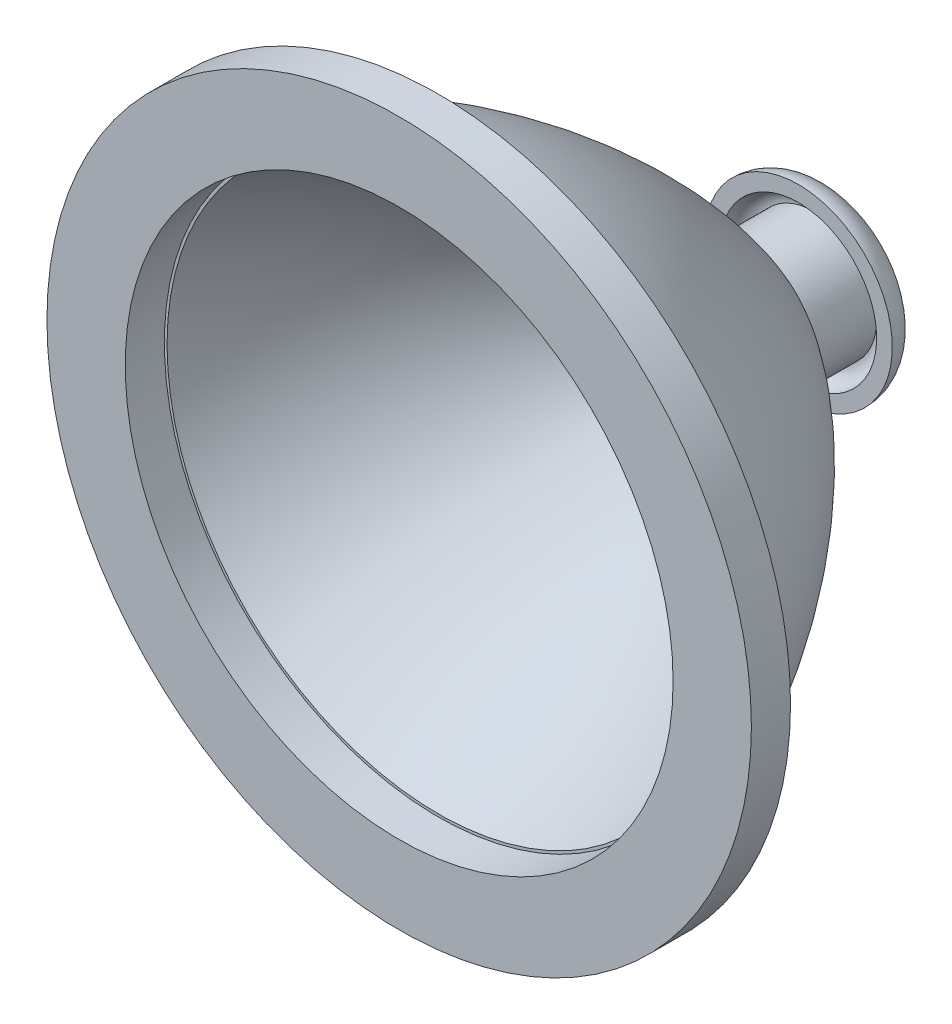
SolidWorks part; units mm, degrees
ref_plane "Front Plane" through (0, 0, 0) normal (0, 0, 1) x (1, 0, 0)
ref_plane "Top Plane" through (0, 0, 0) normal (0, 1, 0) x (1, 0, 0)
ref_plane "Right Plane" through (0, 0, 0) normal (1, 0, 0) x (0, 0, -1)
sketch "Sketch1" plane through (0, 0, 0) normal (1, 0, 0) x (0, 0, -1)
  line L0 (-22.4288, 0) -> (28.5775, 0) construction
  line L1 (0, 0) -> (0, 50.8)
  line L2 (0, 0) -> (50.8, 0)
  line L3 (50.8, 0) -> (50.8, 10.16)
  line L5 (0, 88.99) -> (0, -88.99) construction
  arc A0 (50.8, 10.16) -> (0, 50.8) centre (-34.7283, -44.6804) ccw
  dimension "D3" = 101.6
  dimension "D1" = 50.8
  dimension "D2" = 10.16
revolve "Base Revolve" add sketch "Sketch1" angle 360 about L0
shell "Lens Shell" thickness 6.35
sketch "Sketch2" plane through (0, 0, -50.8) normal (0, 0, -1) x (-1, 0, 0)
  circle A1 centre (0, 0) radius 10.16
  circle A2 centre (0, 0) radius 10.16
  dimension "D1" = 0
extrude "Lens Neck" add sketch "Sketch2" along normal blind 10.16
hole_wizard "Bulb Hole" positions "3DSketch1" profile "Sketch3" counterbore size "1/2" standard "ANSI Inch"
sketch3d "3DSketch1"
  point P0 (0, 0, 0)
  point P4 (0, 0, 0)
  point P6 (0, 0, 0)
  point P8 (0, 0, 0)
  point P10 (0, 0, 0)
  point P12 (0, 0, 0)
  point P14 (0, 0, 0)
  point P16 (0, 0, 0)
  point P18 (0, 0, 0)
  point P20 (0.1526, 0.0379, -44.45)
sketch "Sketch3" plane through (0.1526, 0.0379, -44.45) normal (1, 0, 0) x (0, -1, 0)
  line L0 (0, 0) -> (0, 16.51)
  line L1 (0, 16.51) -> (6.7462, 16.51)
  line L3 (6.7462, 16.51) -> (6.7462, 5.08)
  line L4 (6.7462, 5.08) -> (7.62, 5.08)
  line L5 (7.62, 5.08) -> (7.62, 0)
  line L7 (7.62, 0) -> (0, 0)
  line L11 (0, -6.35) -> (0, 107.95) construction
  dimension "Thru Hole Dia." = 13.4925
  dimension "Thru Hole Depth" = 16.51
  dimension "C'Bore Dia." = 15.24
  dimension "C'Bore Depth" = 5.08
sketch "Sketch4" plane through (0, 0, 0) normal (1, 0, 0) x (0, 0, -1)
  line L0 (60.96, 10.16) -> (50.8, 10.16) construction
  arc A0 (60.96, 10.16) -> (58.42, 12.7) centre (58.42, 10.16) ccw
  dimension "D1" = 2.54
revolve "Revolve-Thin1" add sketch "Sketch4" angle 360 about axis through (0, 0, -60.96) along (0, 0, 1)
sketch "Sketch5" plane through (0, 0, 0) normal (0, 0, 1) x (1, 0, 0)
  circle A2 centre (0, 0) radius 57.15
  circle A3 centre (0, 0) radius 57.15
  circle A4 centre (0, 0) radius 44.45
  circle A5 centre (0, 0) radius 44.45
  dimension "D1" = 6.35
  dimension "D2" = 6.35
extrude "Lens Cover" add sketch "Sketch5" along normal blind 6.35
sketch "Sketch6" plane through (0, 0, 0) normal (0, 0, 1) x (1, 0, 0)
  circle A0 centre (0, 0) radius 44.45 construction
  circle A1 centre (0, 0) radius 44.45
extrude "Lens Shield" [suppressed] add sketch "Sketch6" along normal blind 2.54
